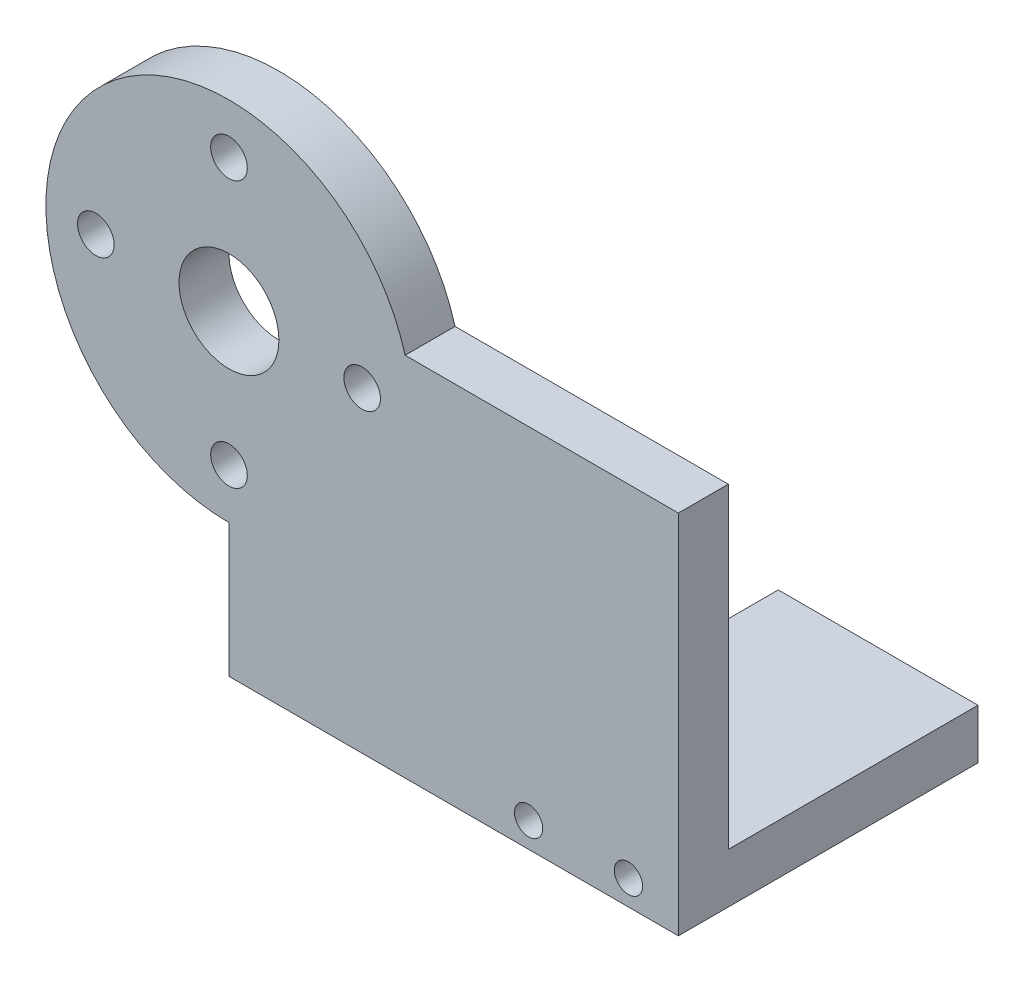
SolidWorks part; units mm, degrees
ref_plane "Front Plane" through (0, 0, 0) normal (0, 0, 1) x (1, 0, 0)
ref_plane "Top Plane" through (0, 0, 0) normal (0, 1, 0) x (1, 0, 0)
ref_plane "Right Plane" through (0, 0, 0) normal (1, 0, 0) x (0, 0, -1)
sketch "Stock_horn_attachment_profile" plane through (0, 0, 0) normal (0, 0, 1) x (1, 0, 0)
  circle A0 centre (0, 0) radius 11
  dimension "D1" = 22
extrude "Stock_horn_attachment" add sketch "Stock_horn_attachment_profile" along normal blind 3 from offset 15
sketch "Finger_arm_profile" plane through (0, 0, 0) normal (0, 0, 1) x (1, 0, 0)
  line L1 (0, -19) -> (27, -19)
  line L2 (0, -19) -> (0, 3)
  line L3 (0, 3) -> (27, 3)
  line L4 (27, -19) -> (27, 3)
  dimension "D1" = 27
  dimension "D2" = 22
extrude "Finger_arm" add sketch "Finger_arm_profile" along normal blind 3 from offset 15
sketch "Descending_contact_finger_profile" plane through (0, 0, 0) normal (0, 0, 1) x (1, 0, 0)
  line L1 (15, -19) -> (27, -19)
  line L2 (15, -19) -> (15, -16)
  line L3 (15, -16) -> (27, -16)
  line L4 (27, -19) -> (27, -16)
  dimension "D1" = 12
  dimension "D2" = 3
extrude "Descending_contact_finger" add sketch "Descending_contact_finger_profile" along normal blind 18
sketch "Horn_center_access_profile" plane through (0, 0, 0) normal (0, 0, 1) x (1, 0, 0)
  circle A0 centre (0, 0) radius 3
  dimension "D1" = 6
extrude "Horn_center_access" cut sketch "Horn_center_access_profile" along normal through all from offset 50
sketch "Horn_screws_profile" plane through (0, 0, 0) normal (0, 0, 1) x (1, 0, 0)
  circle A0 centre (0, -8) radius 1.1
  circle A1 centre (0, 8) radius 1.1
  circle A2 centre (-8, 0) radius 1.1
  circle A3 centre (8, 0) radius 1.1
  dimension "D1" = 2.2
  dimension "D2" = 2.2
  dimension "D3" = 2.2
  dimension "D4" = 2.2
extrude "Horn_screws" cut sketch "Horn_screws_profile" along normal through all from offset 50
sketch "Contact_pad_keeper_profile" plane through (0, 0, 0) normal (0, 0, 1) x (1, 0, 0)
  circle A0 centre (18, -17.5) radius 0.85
  circle A1 centre (24, -17.5) radius 0.85
  dimension "D1" = 1.7
  dimension "D2" = 1.7
extrude "Contact_pad_keeper" cut sketch "Contact_pad_keeper_profile" along normal through all from offset 50
